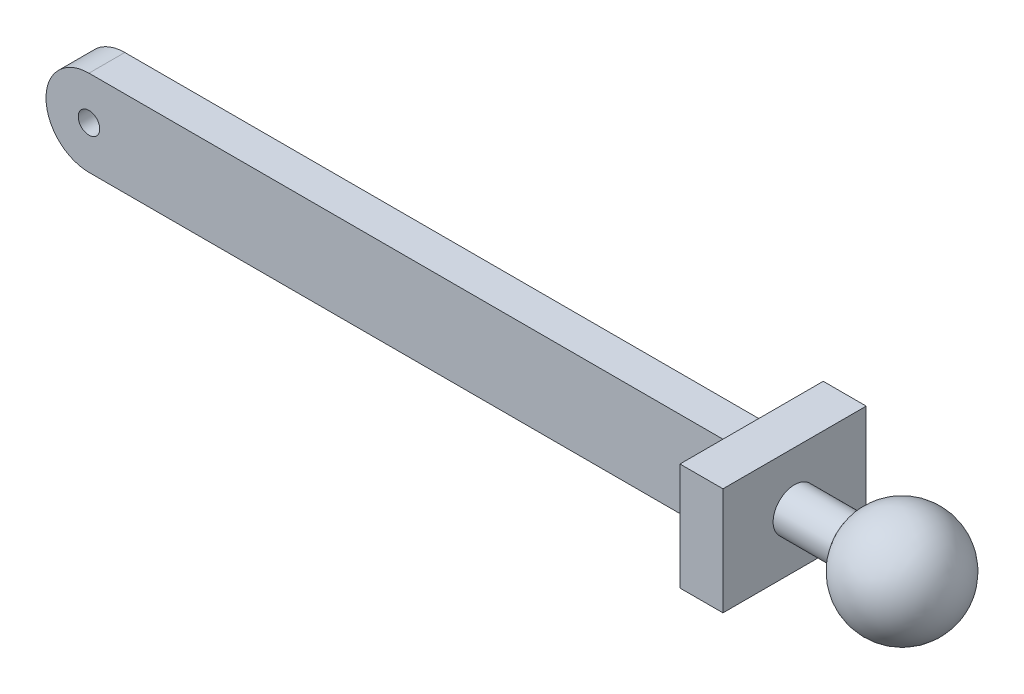
SolidWorks part; units mm, degrees
ref_plane "Front Plane" through (0, 0, 0) normal (0, 0, 1) x (1, 0, 0)
ref_plane "Top Plane" through (0, 0, 0) normal (0, 1, 0) x (1, 0, 0)
ref_plane "Right Plane" through (0, 0, 0) normal (1, 0, 0) x (0, 0, -1)
sketch "Sketch1" plane through (0, 0, 0) normal (0, 0, 1) x (1, 0, 0)
  line L0 (0, 0) -> (90, 0) construction
  line L1 (0, 6) -> (90, 6)
  line L2 (0, -6) -> (90, -6)
  circle A0 centre (0, 0) radius 1.5
  circle A1 centre (90, 0) radius 1.5
  circle A2 centre (0, 0) radius 6
  circle A3 centre (90, 0) radius 6
  dimension "D2" = 3
  dimension "D3" = 3
  dimension "D4" = 12
  dimension "D5" = 12
  dimension "D1" = 90
extrude "Boss-Extrude1" add sketch "Sketch1" along normal blind 5
fillet "Fillet3" radius 1 1 edges at (91.5, 0, 0)
sketch "Sketch2" plane through (0, 0, 5) normal (0, 0, 1) x (1, 0, 0)
  circle A0 centre (90, 0) radius 3
sketch "Sketch4" plane through (0, 0, 5) normal (0, 0, 1) x (1, 0, 0)
  line L1 (90, -7.5) -> (96, -7.5)
  line L2 (90, -7.5) -> (90, 7.5)
  line L3 (90, 7.5) -> (96, 7.5)
  line L4 (96, -7.5) -> (96, 7.5)
  dimension "D1" = 6
  dimension "D2" = 15
  dimension "D3" = 7.5
extrude "Boss-Extrude2" add sketch "Sketch4" against normal blind 20 from offset 7.5
sketch "Sketch5" plane through (96, 0, 0) normal (1, 0, 0) x (0, 0, -1)
  circle A0 centre (-2.5, 0) radius 3
extrude "Boss-Extrude3" add sketch "Sketch5" along normal blind 15
sketch "Sketch6" plane through (111, 0, 0) normal (1, 0, 0) x (0, 0, -1)
  line L0 (-2.5, 0) -> (2.4295, 0) construction
  line L1 (-2.5, 7.5) -> (-2.5, -7.5)
  arc A0 (-2.5, 7.5) -> (-2.5, -7.5) centre (-2.5, 0) cw
revolve "Revolve1" add sketch "Sketch6" angle 360 about L1
